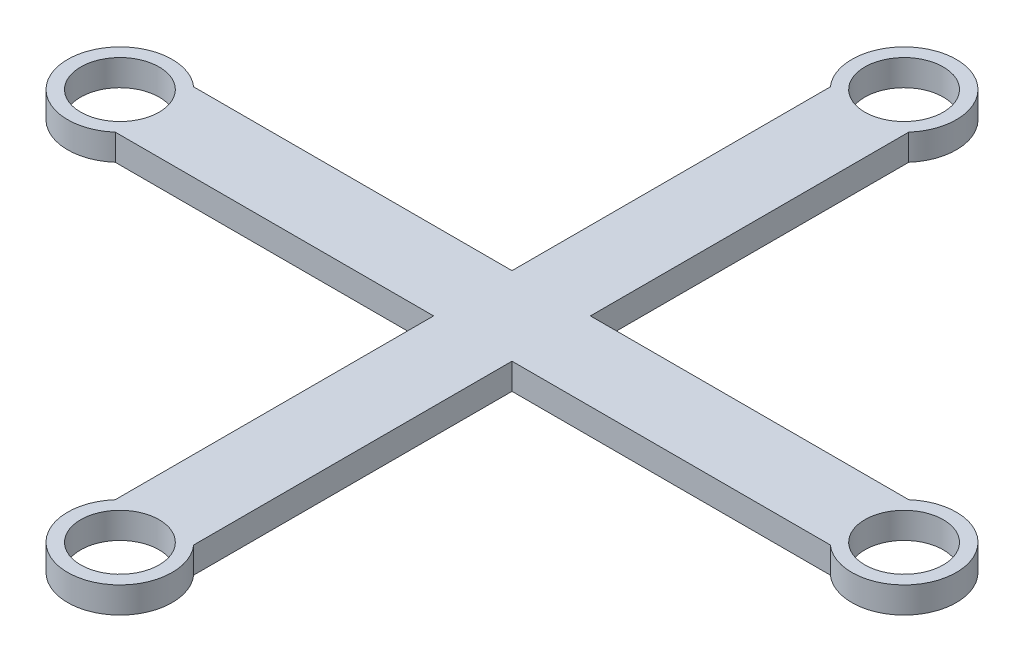
SolidWorks part; units mm, degrees
ref_plane "Front Plane" through (0, 0, 0) normal (0, 0, 1) x (1, 0, 0)
ref_plane "Top Plane" through (0, 0, 0) normal (0, 1, 0) x (1, 0, 0)
ref_plane "Right Plane" through (0, 0, 0) normal (1, 0, 0) x (0, 0, -1)
sketch "Sketch1" plane through (0, 0, 0) normal (0, 1, 0) x (1, 0, 0)
  line L0 (-14.703, -147.0297) -> (-15, -150) construction
  line L1 (-136.7712, 15) -> (136.7712, 15)
  line L3 (-136.7712, -15) -> (136.7712, -15)
  line L8 (15, -136.7712) -> (15, 136.7712)
  line L10 (-15, -136.7712) -> (-15, 136.7712)
  line L11 (15, -150) -> (14.703, -147.0297) construction
  line L12 (15, 150) -> (14.703, 147.0297) construction
  line L13 (-14.703, 147.0297) -> (-15, 150) construction
  line L14 (147.0297, -14.703) -> (150, -15) construction
  line L15 (147.0297, 14.703) -> (150, 15) construction
  circle A0 centre (0, 150) radius 15
  circle A1 centre (150, 0) radius 15
  circle A2 centre (0, -150) radius 15
  circle A3 centre (-150, 0) radius 15
  arc A4 (-136.7712, 15) -> (-136.7712, -15) centre (-150, 0) ccw
  arc A5 (-15, -136.7712) -> (15, -136.7712) centre (0, -150) ccw
  arc A6 (136.7712, -15) -> (136.7712, 15) centre (150, 0) ccw
  arc A7 (15, 136.7712) -> (-15, 136.7712) centre (0, 150) ccw
  circle A8 centre (0, 150) radius 20 construction
  circle A9 centre (150, 0) radius 20 construction
  circle A10 centre (-150, 0) radius 20 construction
  circle A11 centre (0, -150) radius 20 construction
  point P0 (0, 0)
  point P6 (0, 0)
  dimension "D2" = 300
  dimension "D3" = 30
  dimension "D4" = 30
  dimension "D5" = 5
extrude "Boss-Extrude2" add sketch "Sketch1" along normal blind 10 contours L10 A5 L8 L3 A2 | L10 L3 L8 L1 | L8 A7 L10 L1 A0 | L1 A4 L3 L10 A3 | L3 A6 L1 L8 A1
